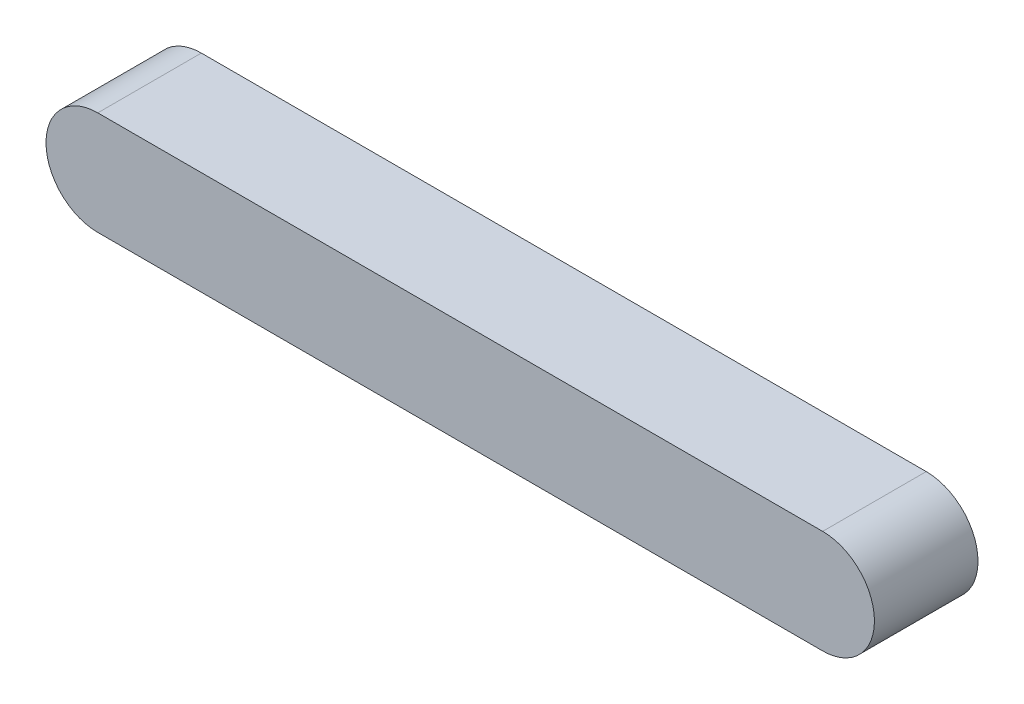
SolidWorks part; units mm, degrees
material "Plain Carbon Steel"
ref_plane "Front Plane" through (0, 0, 0) normal (0, 0, 1) x (1, 0, 0)
ref_plane "Top Plane" through (0, 0, 0) normal (0, 1, 0) x (1, 0, 0)
ref_plane "Right Plane" through (0, 0, 0) normal (1, 0, 0) x (0, 0, -1)
sketch "Sketch1" plane through (0, 0, 0) normal (0, 0, 1) x (1, 0, 0)
  line L0 (-70, 0) -> (70, 0) construction
  line L1 (-70, 10) -> (70, 10)
  line L2 (-70, -10) -> (70, -10)
  line L3 (-40.188, 0) -> (46.724, 0) construction
  line L4 (-80, 0) -> (-80, 16.5501) construction
  line L5 (80, 0) -> (80, 15.8403) construction
  arc A0 (-70, 10) -> (-70, -10) centre (-70, 0) ccw
  arc A1 (70, -10) -> (70, 10) centre (70, 0) ccw
  point P2 (0, 0)
  dimension "D2" = 10
  dimension "D1" = 160
extrude "Boss-Extrude1" add sketch "Sketch1" along normal blind 20
